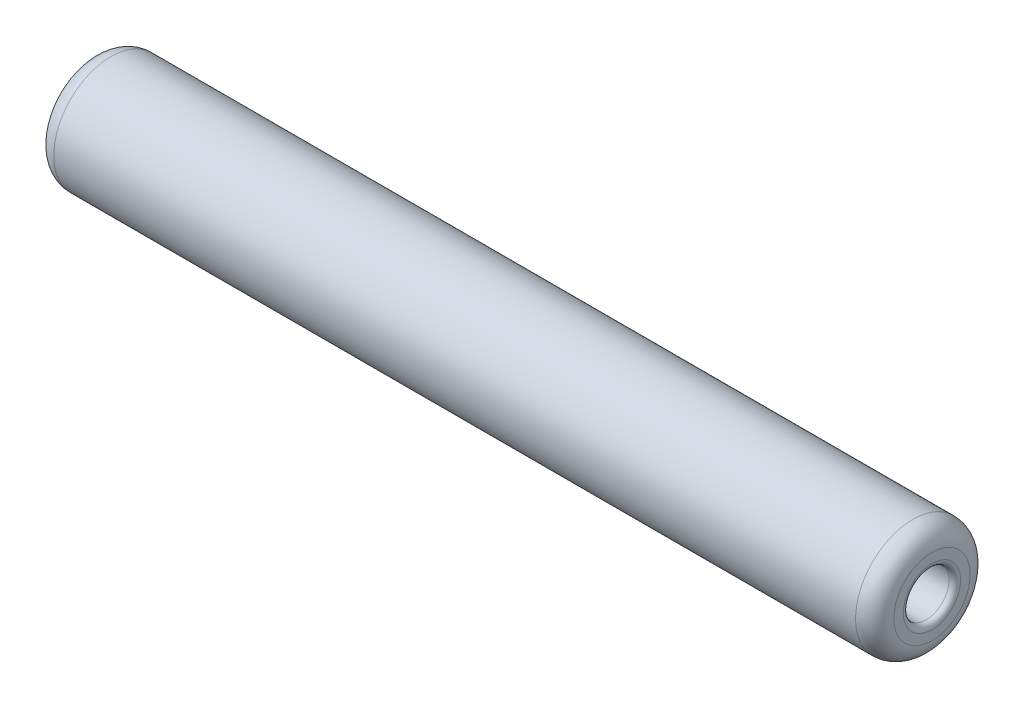
SolidWorks part; units mm, degrees
ref_plane "Front Plane" through (0, 0, 0) normal (0, 0, 1) x (1, 0, 0)
ref_plane "Top Plane" through (0, 0, 0) normal (0, 1, 0) x (1, 0, 0)
ref_plane "Right Plane" through (0, 0, 0) normal (1, 0, 0) x (0, 0, -1)
sketch "草图1" plane through (0, 0, 0) normal (1, 0, 0) x (0, 0, -1)
  circle A0 centre (0, 0) radius 3
  dimension "D1" = 6
extrude "凸台-拉伸1" add sketch "草图1" along normal blind 44 contours A0
sketch "草图2" plane through (0, 0, 0) normal (-1, 0, 0) x (0, 0, 1)
  circle A0 centre (0, 0) radius 1.2
extrude "切除-拉伸1" cut sketch "草图2" against normal blind 44
fillet "圆角1" radius 1 2 edges at (44, 0, -3) (0, 0, -3)
fillet "圆角2" radius 0.3 2 edges at (44, 0, 1.2) (0, 0, 1.2)
